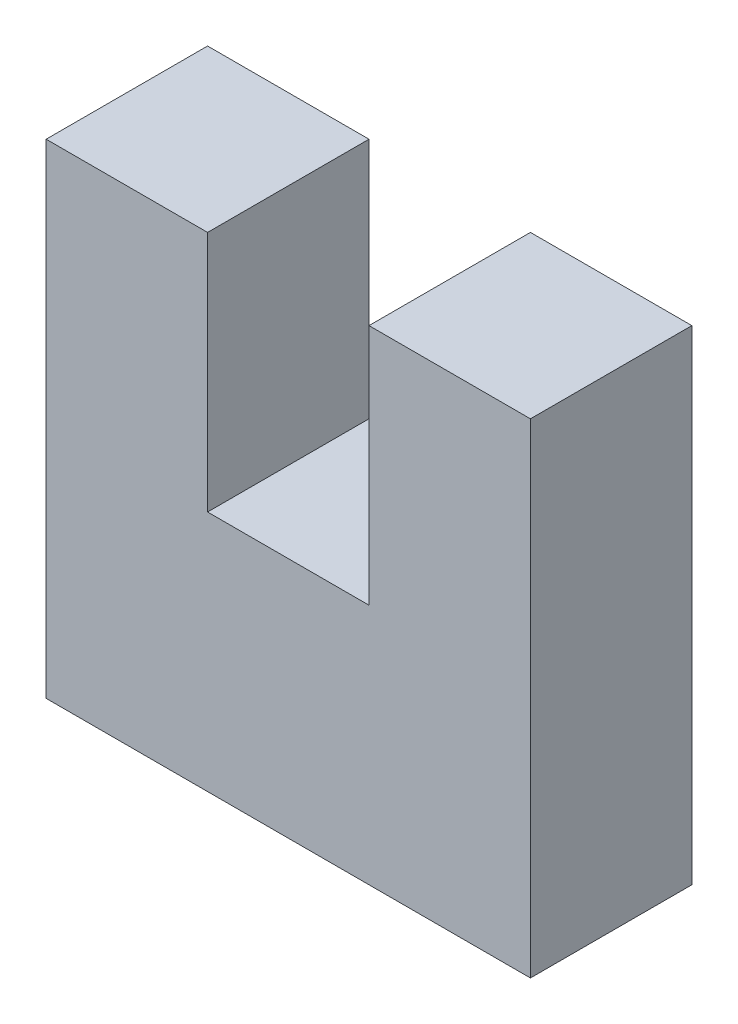
SolidWorks part; units mm, degrees
ref_plane "Front Plane" through (0, 0, 0) normal (0, 0, 1) x (1, 0, 0)
ref_plane "Top Plane" through (0, 0, 0) normal (0, 1, 0) x (1, 0, 0)
ref_plane "Right Plane" through (0, 0, 0) normal (1, 0, 0) x (0, 0, -1)
sketch "Sketch2" plane through (0, 0, 0) normal (0, 0, 1) x (1, 0, 0)
  line L0 (-13.0748, 5.7046) -> (-7.9948, 5.7046)
  line L1 (-7.9948, 5.7046) -> (-7.9948, -1.9154)
  line L2 (-7.9948, -1.9154) -> (-2.9148, -1.9154)
  line L3 (-2.9148, -1.9154) -> (-2.9148, 5.7046)
  line L4 (-2.9148, 5.7046) -> (2.1652, 5.7046)
  line L5 (2.1652, 5.7046) -> (2.1652, -9.5354)
  line L6 (2.1652, -9.5354) -> (-13.0748, -9.5354)
  line L7 (-13.0748, -9.5354) -> (-13.0748, 5.7046)
  dimension "D1" = 5.08
  dimension "D2" = 5.08
  dimension "D3" = 15.24
  dimension "D4" = 15.24
  dimension "D5" = 15.24
  dimension "D6" = 7.62
extrude "Boss-Extrude1" add sketch "Sketch2" along normal blind 5.08
